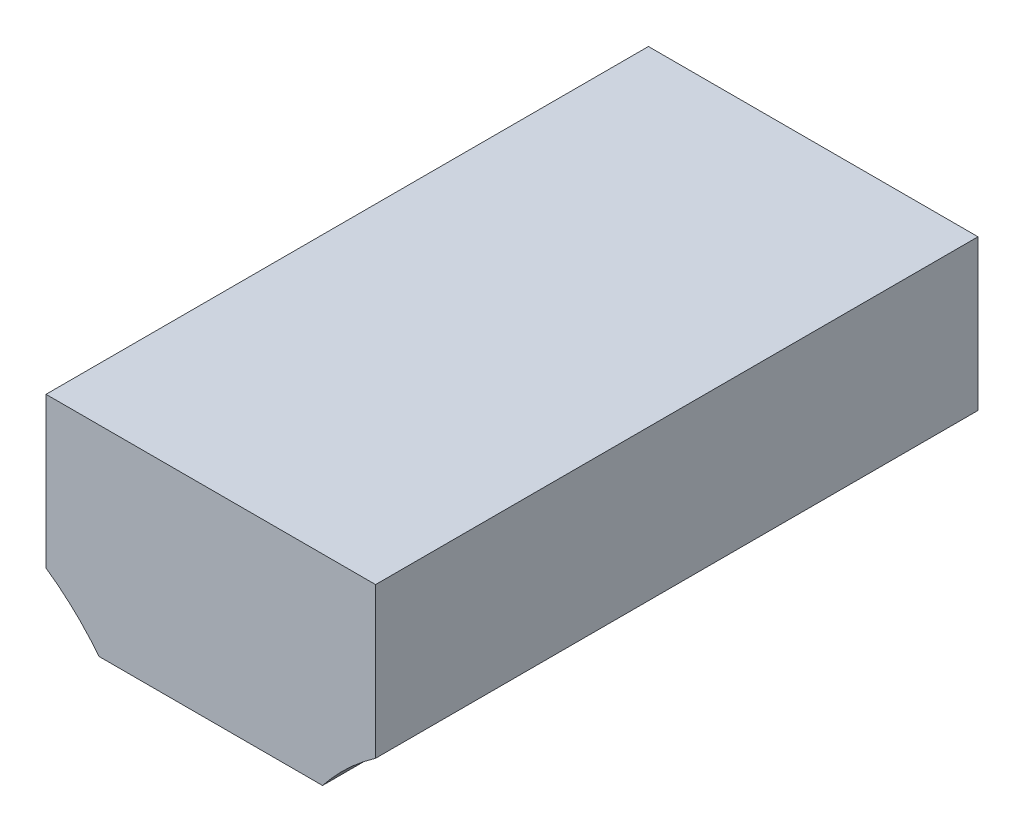
SolidWorks part; units mm, degrees
ref_plane "Спереди" through (0, 0, 0) normal (0, 0, 1) x (1, 0, 0)
ref_plane "Сверху" through (0, 0, 0) normal (0, 1, 0) x (1, 0, 0)
ref_plane "Справа" through (0, 0, 0) normal (1, 0, 0) x (0, 0, -1)
sketch "Эскиз1" plane through (0, 0, 0) normal (0, 0, 1) x (1, 0, 0)
  line L0 (0, 6.6649) -> (0, 17.2186) construction
  line L1 (-10.959, 5.9777) -> (10.959, 5.9777)
  line L2 (-10.959, 5.9777) -> (-10.959, -4.0278)
  line L3 (-7.4322, -7.3588) -> (7.4322, -7.3588)
  line L4 (10.959, 5.9777) -> (10.959, -4.0278)
  arc A0 (10.959, -4.0278) -> (7.4322, -7.3588) centre (20.4149, -17.572) ccw
  arc A1 (-10.959, -4.0278) -> (-7.4322, -7.3588) centre (-20.4149, -17.572) cw
  point P0 (0, 0)
extrude "Вытянуть1" add sketch "Эскиз1" along normal up to surface (40.0645 mm away) from surface at -10.0645
sketch "Эскиз2" plane through (0, -7.3588, 0) normal (0, -1, 0) x (1, 0, 0)
  line L0 (7.4322, 30) -> (7.4322, -10.0645) construction
  line L1 (-7.4322, -10.0645) -> (7.4322, -10.0645) construction
  circle A0 centre (0, 9.9677) radius 5.5
  dimension "D1" = 11
  dimension "D2" = 7.4322
  dimension "D3" = 20.0323
extrude "Вытянуть2" cut sketch "Эскиз2" against normal blind 5.5
sketch "Эскиз3" plane through (0, -1.8588, 0) normal (0, -1, 0) x (1, 0, 0)
  circle A0 centre (0, 9.9677) radius 2
extrude "Вытянуть3" cut sketch "Эскиз3" against normal blind 4
